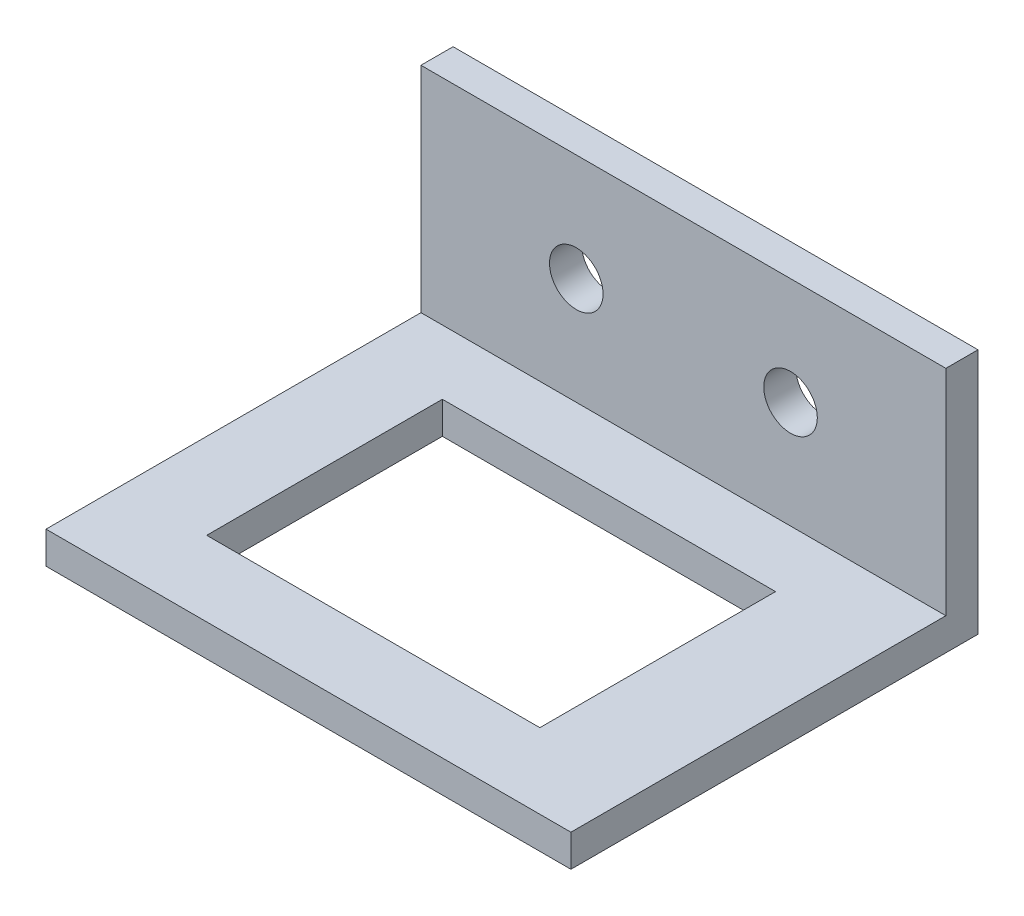
SolidWorks part; units mm, degrees
ref_plane "Front Plane" through (0, 0, 0) normal (0, 0, 1) x (1, 0, 0)
ref_plane "Top Plane" through (0, 0, 0) normal (0, 1, 0) x (1, 0, 0)
ref_plane "Right Plane" through (0, 0, 0) normal (1, 0, 0) x (0, 0, -1)
sketch "Sketch1" plane through (0, 0, 0) normal (1, 0, 0) x (0, 0, -1)
  line L7 (-38, 0) -> (0, 0)
  line L12 (0, 0) -> (0, 23)
  line L13 (0, 23) -> (-3, 23)
  line L14 (-3, 23) -> (-3, 3)
  line L15 (-3, 3) -> (-38, 3)
  line L16 (-38, 3) -> (-38, 0)
  dimension "D1" = 3
  dimension "D2" = 35
  dimension "D3" = 3
  dimension "D4" = 20
extrude "Boss-Extrude1" add sketch "Sketch1" along normal blind 49
sketch "Sketch7" plane through (0, 3, 0) normal (0, 1, 0) x (1, 0, 0)
  line L0 (49, -3) -> (0, -3) construction
  line L1 (8, -9) -> (39.1, -9)
  line L2 (8, -9) -> (8, -31)
  line L3 (8, -31) -> (39.1, -31)
  line L4 (39.1, -9) -> (39.1, -31)
  line L5 (0, -3) -> (0, -38) construction
  dimension "D1" = 22
  dimension "D2" = 31.1
  dimension "D3" = 6
  dimension "D4" = 8
extrude "Cut-Extrude5" cut sketch "Sketch7" against normal up to surface (3 mm away) up to face at (24.5, 0, 19)
sketch "Sketch8" plane through (0, 0, 3) normal (0, 0, 1) x (1, 0, 0)
  line L0 (0, 13) -> (49, 13) construction
  line L1 (0, 23) -> (0, 3) construction
  line L2 (49, 23) -> (49, 3) construction
  line L3 (24.5, 13) -> (24.5, 3) construction
  line L4 (49, 3) -> (0, 3) construction
  circle A0 centre (14.5, 13) radius 2.5
  circle A1 centre (34.5, 13) radius 2.5
  point P14 (0, 0)
  dimension "D1" = 5
  dimension "D2" = 5
  dimension "D3" = 20
extrude "Cut-Extrude6" cut sketch "Sketch8" against normal up to surface (3 mm away) up to face at (24.5, 11.5, 0)
